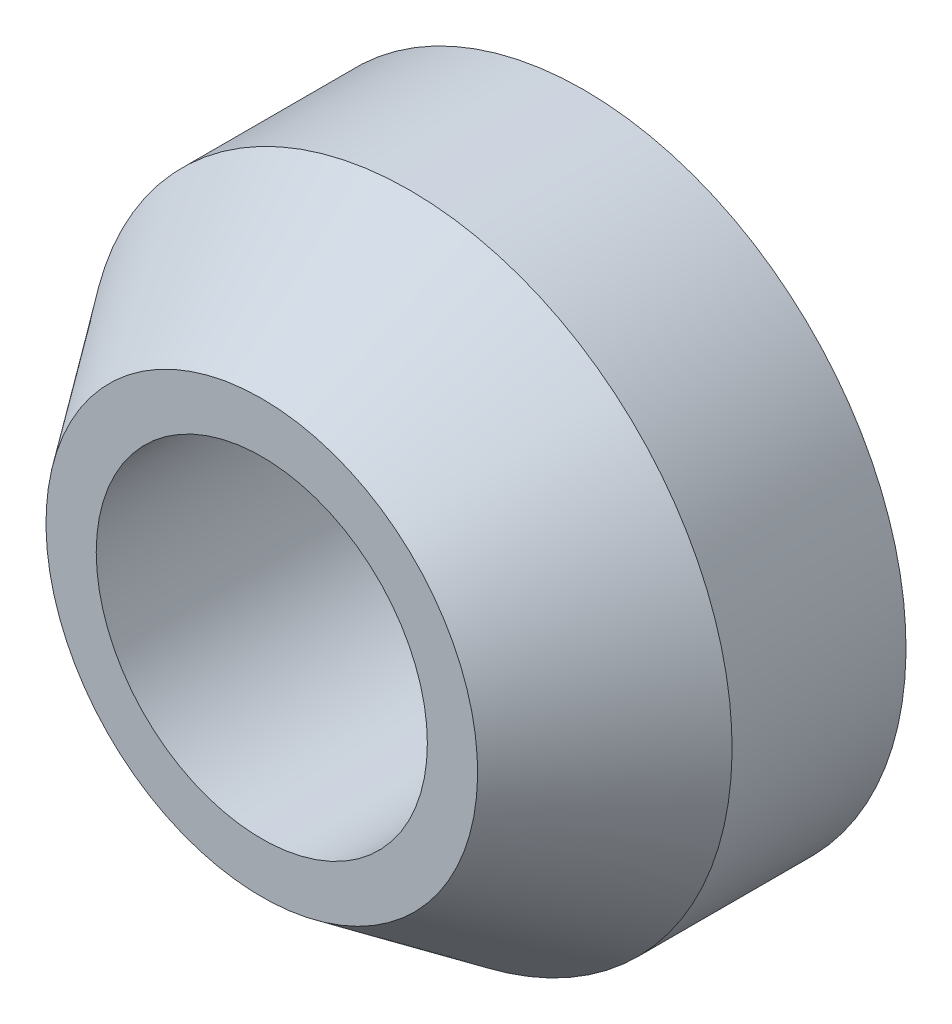
SolidWorks part; units mm, degrees
material "AISI 1045 Steel, cold drawn"
ref_plane "X-Y Datum" through (0, 0, 0) normal (0, 0, 1) x (1, 0, 0)
ref_plane "X-Z Datum" through (0, 0, 0) normal (0, 1, 0) x (1, 0, 0)
ref_plane "Y-Z Datum" through (0, 0, 0) normal (1, 0, 0) x (0, 0, -1)
sketch "Sketch1" plane through (0, 0, 0) normal (1, 0, 0) x (0, 0, -1)
  line L1 (-6.35, 0) -> (-6.35, 4.2545)
  line L2 (-6.35, 4.2545) -> (-3.429, 6.35)
  line L3 (-3.429, 6.35) -> (0, 6.35)
  line L4 (0, 6.35) -> (0, 0)
  line L5 (0, 0) -> (-6.35, 0)
  point P0 (0, 3.175)
  dimension "D1" = 6.35
  dimension "D2" = 6.35
  dimension "D3" = 4.2545
  dimension "D4" = 3.429
revolve "Revolve1" add sketch "Sketch1" angle 360 about L5
hole_wizard "1/4 Clearance Hole1" positions "Sketch2" profile "Sketch3" hole size "1/4" standard "ANSI Inch" end condition through all
sketch "Sketch2" plane through (0, 0, 6.35) normal (0, 0, 1) x (1, 0, 0)
  point P0 (0, 0)
sketch "Sketch3" plane through (0, 0, 6.35) normal (1, 0, 0) x (0, -1, 0)
  line L0 (0, 0) -> (0, 6.35)
  line L1 (0, 6.35) -> (3.2639, 6.35)
  line L2 (3.2639, 6.35) -> (3.2639, 0)
  line L5 (3.2639, 0) -> (0, 0)
  line L11 (0, -6.35) -> (0, 107.95) construction
  dimension "Thru Hole Dia." = 6.5278
  dimension "Thru Hole Depth" = 6.35
